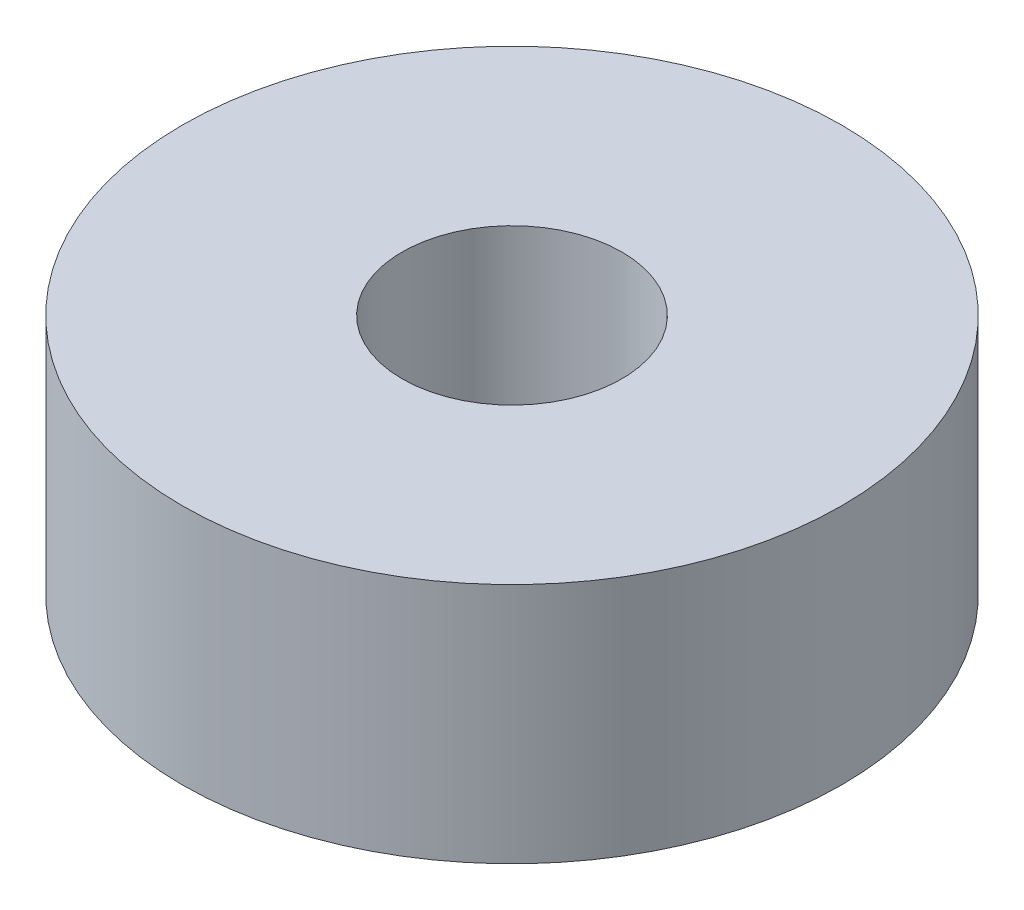
SolidWorks part; units mm, degrees
ref_plane "Front Plane" through (0, 0, 0) normal (0, 0, 1) x (1, 0, 0)
ref_plane "Top Plane" through (0, 0, 0) normal (0, 1, 0) x (1, 0, 0)
ref_plane "Right Plane" through (0, 0, 0) normal (1, 0, 0) x (0, 0, -1)
sketch "Sketch1" plane through (0, 0, 0) normal (0, 1, 0) x (1, 0, 0)
  circle A0 centre (0, 0) radius 19.05
  circle A1 centre (0, 0) radius 6.35
  dimension "D1" = 38.1
  dimension "D2" = 12.7
extrude "Boss-Extrude1" add sketch "Sketch1" along normal blind 13.97
fillet "Fillet1" [suppressed] radius 2.54
